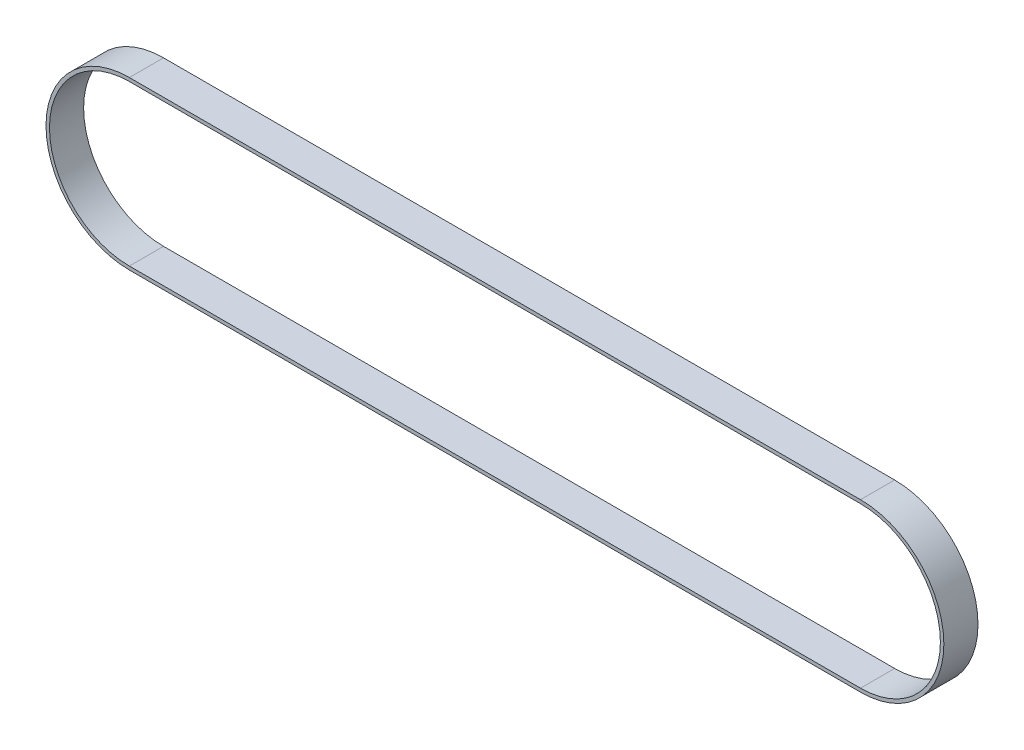
SolidWorks part; units mm, degrees
material "VITON"
ref_plane "Front Plane" through (0, 0, 0) normal (0, 0, 1) x (1, 0, 0)
ref_plane "Top Plane" through (0, 0, 0) normal (0, 1, 0) x (1, 0, 0)
ref_plane "Right Plane" through (0, 0, 0) normal (1, 0, 0) x (0, 0, -1)
sketch "Sketch1" plane through (0, 0, 0) normal (0, 0, 1) x (1, 0, 0)
  line L0 (0, 35.052) -> (-320.802, 35.052)
  line L1 (0, -35.052) -> (-320.802, -35.052)
  line L2 (0, 36.576) -> (-320.802, 36.576)
  line L3 (0, -36.576) -> (-320.802, -36.576)
  arc A0 (0, 35.052) -> (0, -35.052) centre (0, 0) cw
  arc A1 (-320.802, 35.052) -> (-320.802, -35.052) centre (-320.802, 0) ccw
  arc A2 (0, 36.576) -> (0, -36.576) centre (0, 0) cw
  arc A3 (-320.802, 36.576) -> (-320.802, -36.576) centre (-320.802, 0) ccw
  dimension "D1" = 35.052
  dimension "D3" = 1.524
  dimension "D5" = 36.576
  dimension "D2" = 320.802
  dimension "D4" = 1.524
  dimension "D6" = 320.802
  dimension "D7" = 320.802
extrude "Boss-Extrude1" add sketch "Sketch1" along normal blind 14.986
